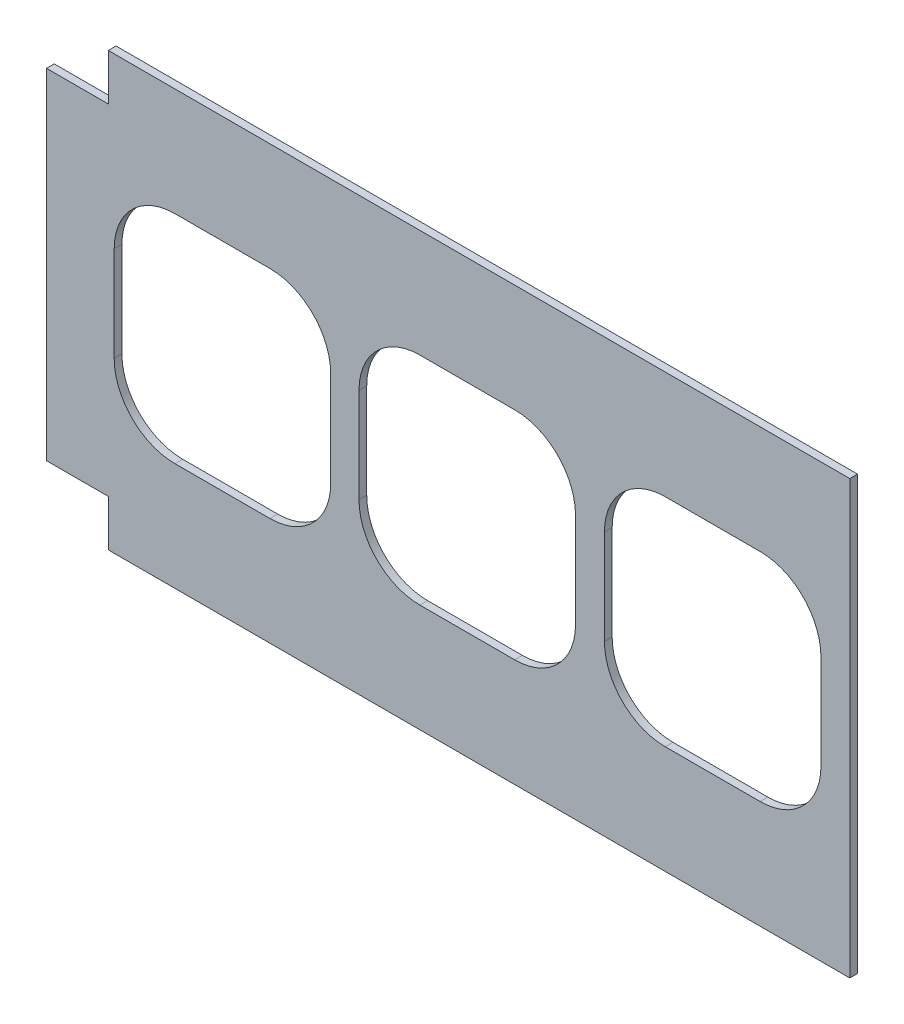
SolidWorks part; units mm, degrees
material "Chrome Stainless Steel"
ref_plane "Front Plane" through (0, 0, 0) normal (0, 0, 1) x (1, 0, 0)
ref_plane "Top Plane" through (0, 0, 0) normal (0, 1, 0) x (1, 0, 0)
ref_plane "Right Plane" through (0, 0, 0) normal (1, 0, 0) x (0, 0, -1)
sketch "Sketch1" plane through (0, 0, 0) normal (0, 0, 1) x (1, 0, 0)
  line L0 (-152.4, 69.85) -> (-177.8, 69.85)
  line L1 (-152.4, -88.9) -> (152.4, -88.9)
  line L2 (-152.4, -88.9) -> (-152.4, -69.85)
  line L3 (-152.4, 88.9) -> (152.4, 88.9)
  line L4 (152.4, -88.9) -> (152.4, 88.9)
  line L5 (-152.4, -88.9) -> (152.4, 88.9) construction
  line L6 (-152.4, 88.9) -> (152.4, -88.9) construction
  line L7 (51.55, -44.5) -> (140.55, -44.5)
  line L8 (51.55, -44.5) -> (51.55, 44.5)
  line L9 (51.55, 44.5) -> (140.55, 44.5)
  line L10 (140.55, -44.5) -> (140.55, 44.5)
  line L11 (51.55, -44.5) -> (140.55, 44.5) construction
  line L12 (51.55, 44.5) -> (140.55, -44.5) construction
  line L13 (-60.974, -44.5) -> (-149.974, -44.5)
  line L14 (-60.974, -44.5) -> (-60.974, 44.5)
  line L15 (-60.974, 44.5) -> (-149.974, 44.5)
  line L16 (-149.974, -44.5) -> (-149.974, 44.5)
  line L17 (-60.974, -44.5) -> (-149.974, 44.5) construction
  line L18 (-60.974, 44.5) -> (-149.974, -44.5) construction
  line L19 (39.661, -44.5) -> (-49.339, -44.5)
  line L20 (39.661, -44.5) -> (39.661, 44.5)
  line L21 (39.661, 44.5) -> (-49.339, 44.5)
  line L22 (-49.339, -44.5) -> (-49.339, 44.5)
  line L23 (39.661, -44.5) -> (-49.339, 44.5) construction
  line L24 (39.661, 44.5) -> (-49.339, -44.5) construction
  line L25 (-177.8, 69.85) -> (152.4, 69.85) construction
  line L26 (-177.8, 69.85) -> (-177.8, -69.85)
  line L27 (-177.8, -69.85) -> (-152.4, -69.85)
  line L28 (152.4, -69.85) -> (-177.8, -69.85) construction
  line L29 (-152.4, 69.85) -> (-152.4, 88.9)
  point P0 (0, 0)
  point P6 (96.05, 0)
  point P11 (-105.474, 0)
  point P18 (-4.839, 0)
  dimension "D1" = 177.8
  dimension "D2" = 304.8
  dimension "D3" = 89
extrude "Boss-Extrude1" add sketch "Sketch1" along normal blind 3.175
fillet "Fillet1" radius 25 12 edges at (140.55, -44.5, 1.5875) (51.55, -44.5, 1.5875) (51.55, 44.5, 1.5875) (140.55, 44.5, 1.5875) (-149.974, 44.5, 1.5875) (-149.974, -44.5, 1.5875) (-60.974, -44.5, 1.5875) (-60.974, 44.5, 1.5875) (-49.339, 44.5, 1.5875) (39.661, 44.5, 1.5875) (39.661, -44.5, 1.5875) (-49.339, -44.5, 1.5875)
